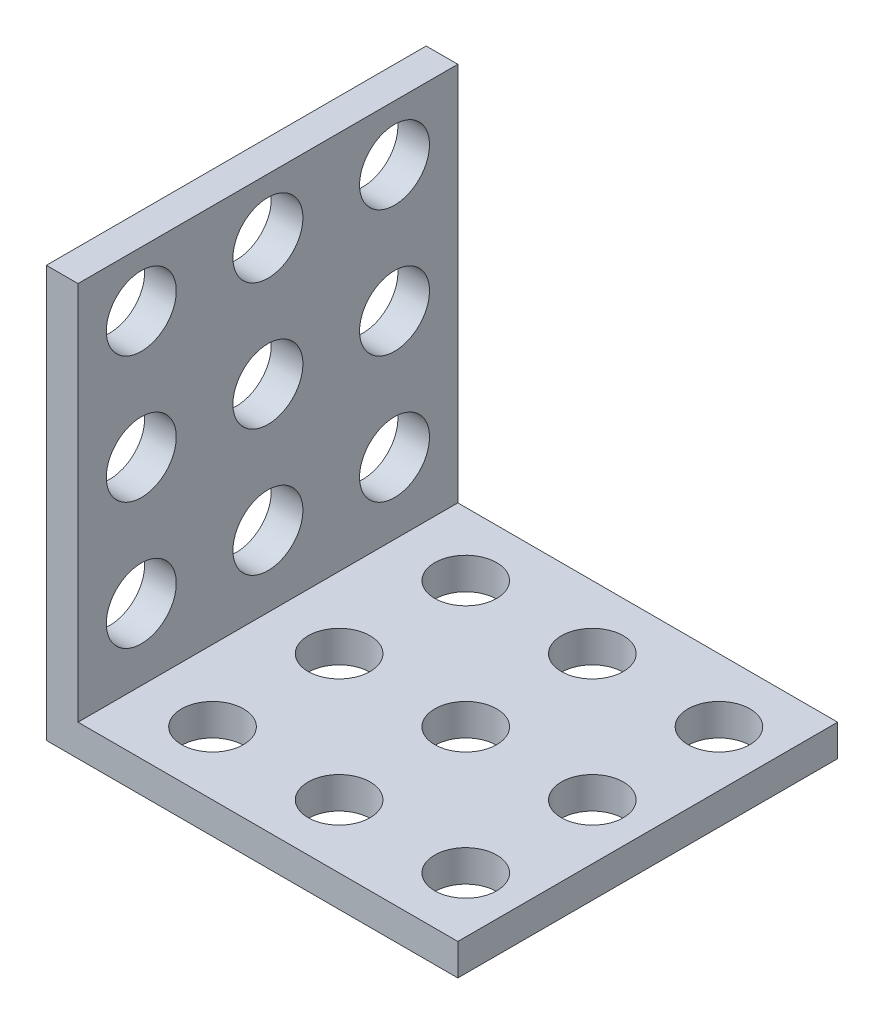
SolidWorks part; units mm, degrees
ref_plane "前视基准面" through (0, 0, 0) normal (0, 0, 1) x (1, 0, 0)
ref_plane "上视基准面" through (0, 0, 0) normal (0, 1, 0) x (1, 0, 0)
ref_plane "右视基准面" through (0, 0, 0) normal (1, 0, 0) x (0, 0, -1)
sketch "草图1" plane through (0, 0, 0) normal (0, 1, 0) x (1, 0, 0)
  line L1 (-12.7364, -12.2433) -> (13.2636, -12.2433)
  line L2 (-12.7364, -12.2433) -> (-12.7364, 11.7567)
  line L3 (-12.7364, 11.7567) -> (13.2636, 11.7567)
  line L4 (13.2636, -12.2433) -> (13.2636, 11.7567)
  circle A0 centre (9.7636, -8.2433) radius 1.9594
  circle A1 centre (9.7636, -0.2433) radius 1.9594
  circle A2 centre (9.7636, 7.7567) radius 1.9594
  circle A3 centre (1.7636, -8.2433) radius 1.9594
  circle A4 centre (1.7636, -0.2433) radius 1.9594
  circle A5 centre (1.7636, 7.7567) radius 1.9594
  circle A6 centre (-6.2364, -8.2433) radius 1.9594
  circle A7 centre (-6.2364, -0.2433) radius 1.9594
  circle A8 centre (-6.2364, 7.7567) radius 1.9594
  point P0 (0, 0)
  dimension "D1" = 4
  dimension "D2" = 3.5
  dimension "D3" = 26
  dimension "D4" = 24
  dimension "D5" = 3
  dimension "D6" = 3
extrude "凸台-拉伸1" add sketch "草图1" along normal blind 26
sketch "草图2" plane through (0, 26, 0) normal (0, 1, 0) x (1, 0, 0)
  line L1 (13.2636, 11.7567) -> (-12.7364, 11.7567) construction
  line L2 (-12.7364, -12.2433) -> (13.2636, -12.2433) construction
  line L5 (-10.7364, 11.7567) -> (13.2636, 11.7567)
  line L6 (-10.7364, 11.7567) -> (-10.7364, -12.2433)
  line L7 (-10.7364, -12.2433) -> (13.2636, -12.2433)
  line L8 (13.2636, 11.7567) -> (13.2636, -12.2433)
extrude "切除-拉伸1" cut sketch "草图2" against normal blind 24
sketch "草图3" plane through (-12.7364, 0, 0) normal (-1, 0, 0) x (0, 0, 1)
  line L0 (-11.7567, 26) -> (12.2433, 26) construction
  line L1 (-11.7567, 26) -> (-11.7567, 0) construction
  circle A0 centre (-7.7567, 22.5) radius 2.2108
  circle A1 centre (0.2433, 22.5) radius 2.2108
  circle A2 centre (8.2433, 22.5) radius 2.2108
  circle A3 centre (-7.7567, 14.5) radius 2.2108
  circle A4 centre (0.2433, 14.5) radius 2.2108
  circle A5 centre (8.2433, 14.5) radius 2.2108
  circle A6 centre (-7.7567, 6.5) radius 2.2108
  circle A7 centre (0.2433, 6.5) radius 2.2108
  circle A8 centre (8.2433, 6.5) radius 2.2108
  dimension "D1" = 3.5
  dimension "D2" = 4
  dimension "D3" = 3
  dimension "D4" = 3
extrude "切除-拉伸2" cut sketch "草图3" against normal blind 24
